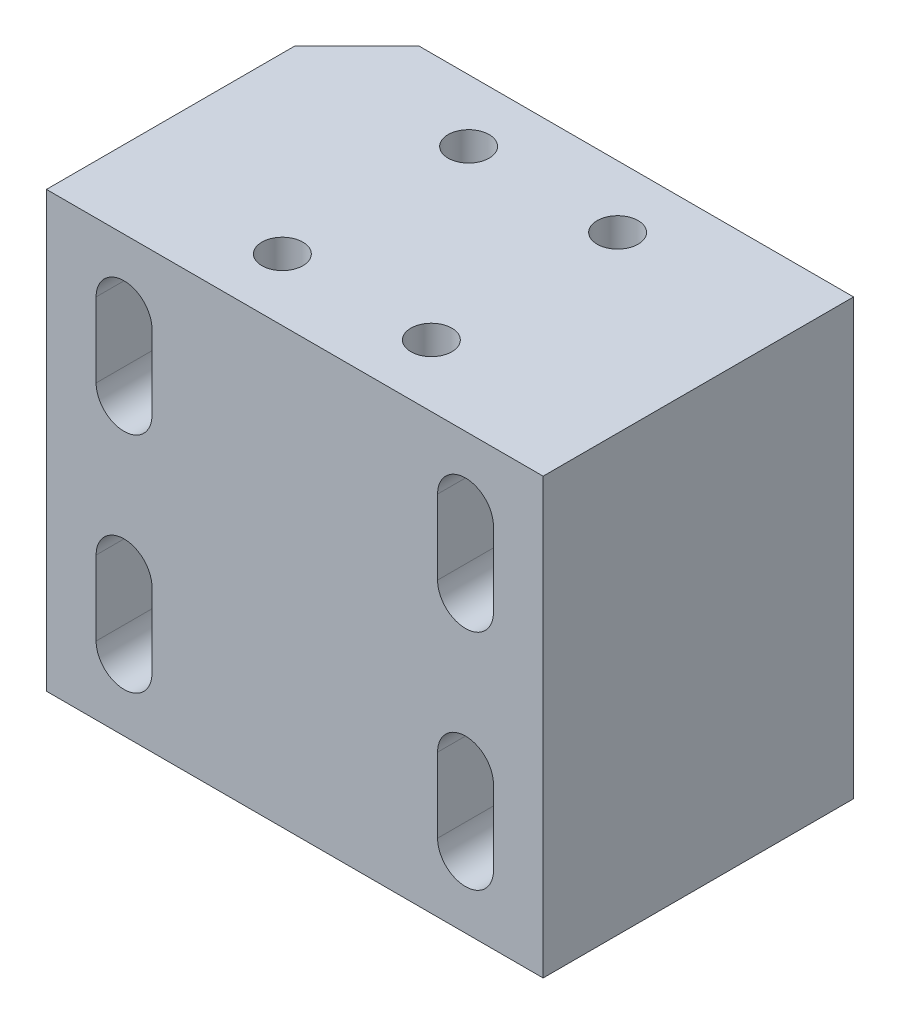
SolidWorks part; units mm, degrees
material "6061 Alloy"
ref_plane "Front Plane" through (0, 0, 0) normal (0, 0, 1) x (1, 0, 0)
ref_plane "Top Plane" through (0, 0, 0) normal (0, 1, 0) x (1, 0, 0)
ref_plane "Right Plane" through (0, 0, 0) normal (1, 0, 0) x (0, 0, -1)
sketch "Sketch1" plane through (0, 0, 0) normal (0, 0, 1) x (1, 0, 0)
  line L5 (-20, -17.5) -> (20, -17.5)
  line L6 (-20, -17.5) -> (-20, 17.5)
  line L7 (-20, 17.5) -> (20, 17.5)
  line L8 (20, -17.5) -> (20, 17.5)
  line L9 (-20, -17.5) -> (20, 17.5) construction
  line L10 (-20, 17.5) -> (20, -17.5) construction
  point P0 (0, 0)
  dimension "D1" = 35
  dimension "D2" = 40
extrude "Boss-Extrude1" add sketch "Sketch1" along normal blind 25 contours L7 L8 L5 L6
chamfer "Chamfer1" distance 5 angle 45 1 edges at (-20, 0, 0)
hole_wizard "CBORE for M4 Hexagon socket head cap screws1" positions "Sketch3" profile "Sketch4" counterbore size "M4" standard "GB" end condition through all
sketch "Sketch3" plane through (0, 0, 0) normal (0, 0, -1) x (-1, 0, 0)
  line L0 (-20, -17.5) -> (-20, 17.5) construction
  line L1 (15, 17.5) -> (-20, 17.5) construction
  line L2 (55, 0) -> (-55, 0) construction
  line L3 (0, 55) -> (0, -55) construction
  point P0 (-13.75, 9)
  point P13 (-13.75, -9)
  point P17 (13.75, -9)
  point P18 (13.75, 9)
  dimension "D1" = 6.25
  dimension "D2" = 8.5
sketch "Sketch4" plane through (13.75, 9, 0) normal (1, 0, 0) x (0, 1, 0)
  line L0 (0, 0) -> (0, 25)
  line L1 (0, 25) -> (2.25, 25)
  line L3 (2.25, 25) -> (2.25, 18)
  line L4 (2.25, 18) -> (4, 18)
  line L5 (4, 18) -> (4, 0)
  line L7 (4, 0) -> (0, 0)
  line L11 (0, -6.35) -> (0, 107.95) construction
  dimension "Thru Hole Dia." = 4.5
  dimension "Thru Hole Depth" = 25
  dimension "C'Bore Dia." = 8
  dimension "C'Bore Depth" = 18
sketch "Sketch5" plane through (0, 0, 18) normal (0, 0, -1) x (-1, 0, 0)
  line L0 (-13.75, 12) -> (-13.75, 6) construction
  line L1 (-9.75, 12) -> (-9.75, 6)
  line L2 (-17.75, 12) -> (-17.75, 6)
  line L3 (55, 0) -> (-55, 0) construction
  line L4 (-13.75, -12) -> (-13.75, -6) construction
  line L5 (-9.75, -12) -> (-9.75, -6)
  line L6 (-17.75, -12) -> (-17.75, -6)
  line L7 (0, 55) -> (0, -55) construction
  line L8 (13.75, 12) -> (13.75, 6) construction
  line L9 (9.75, 12) -> (9.75, 6)
  line L10 (17.75, 12) -> (17.75, 6)
  line L11 (13.75, -12) -> (13.75, -6) construction
  line L12 (9.75, -12) -> (9.75, -6)
  line L13 (17.75, -12) -> (17.75, -6)
  arc A0 (-9.75, 12) -> (-17.75, 12) centre (-13.75, 12) ccw
  arc A1 (-17.75, 6) -> (-9.75, 6) centre (-13.75, 6) ccw
  circle A2 centre (-13.75, 9) radius 4 construction
  arc A3 (-9.75, -12) -> (-17.75, -12) centre (-13.75, -12) cw
  arc A4 (-17.75, -6) -> (-9.75, -6) centre (-13.75, -6) cw
  arc A5 (9.75, 12) -> (17.75, 12) centre (13.75, 12) cw
  arc A6 (17.75, 6) -> (9.75, 6) centre (13.75, 6) cw
  arc A7 (9.75, -12) -> (17.75, -12) centre (13.75, -12) ccw
  arc A8 (17.75, -6) -> (9.75, -6) centre (13.75, -6) ccw
  point P2 (-13.75, 9)
  point P14 (-13.75, -9)
  point P23 (13.75, 9)
  point P30 (13.75, -9)
  dimension "D1" = 6
extrude "Cut-Extrude1" cut sketch "Sketch5" along normal through all
sketch "Sketch6" plane through (0, 0, 18) normal (0, 0, -1) x (-1, 0, 0)
  line L0 (-13.75, 12) -> (-13.75, 6) construction
  line L1 (-11.5, 12) -> (-11.5, 6)
  line L2 (-16, 12) -> (-16, 6)
  line L3 (0, 55) -> (0, -55) construction
  line L4 (13.75, 12) -> (13.75, 6) construction
  line L5 (11.5, 12) -> (11.5, 6)
  line L6 (16, 12) -> (16, 6)
  line L7 (55, 0) -> (-55, 0) construction
  line L8 (-13.75, -12) -> (-13.75, -6) construction
  line L9 (-11.5, -12) -> (-11.5, -6)
  line L10 (-16, -12) -> (-16, -6)
  line L11 (13.75, -12) -> (13.75, -6) construction
  line L12 (11.5, -12) -> (11.5, -6)
  line L13 (16, -12) -> (16, -6)
  arc A0 (-11.5, 12) -> (-16, 12) centre (-13.75, 12) ccw
  arc A1 (-16, 6) -> (-11.5, 6) centre (-13.75, 6) ccw
  circle A2 centre (-13.75, 9) radius 2.25 construction
  arc A3 (-9.75, 12) -> (-17.75, 12) centre (-13.75, 12) ccw construction
  arc A4 (11.5, 12) -> (16, 12) centre (13.75, 12) cw
  arc A5 (16, 6) -> (11.5, 6) centre (13.75, 6) cw
  arc A6 (-11.5, -12) -> (-16, -12) centre (-13.75, -12) cw
  arc A7 (-16, -6) -> (-11.5, -6) centre (-13.75, -6) cw
  arc A8 (11.5, -12) -> (16, -12) centre (13.75, -12) ccw
  arc A9 (16, -6) -> (11.5, -6) centre (13.75, -6) ccw
  point P2 (-13.75, 9)
  point P18 (13.75, 9)
  point P27 (-13.75, -9)
  point P34 (13.75, -9)
extrude "Cut-Extrude2" cut sketch "Sketch6" against normal through all
hole_wizard "M4 Tapped Hole1" positions "Sketch7" profile "Sketch8" tap size "M4" standard "GB" end condition through all
sketch "Sketch7" plane through (0, 17.5, 0) normal (0, 1, 0) x (1, 0, 0)
  line L0 (0, -13.75) -> (0, 13.75) construction
  line L1 (-20, -25) -> (20, -25) construction
  point P0 (-6, -5)
  point P4 (-6, -20)
  point P9 (6, -20)
  point P10 (6, -5)
  dimension "D1" = 15
  dimension "D2" = 12
  dimension "D3" = 5
sketch "Sketch8" plane through (-6, 17.5, 5) normal (1, 0, 0) x (0, 0, 1)
  line L0 (0, 0) -> (0, 35)
  line L1 (0, 35) -> (1.65, 35)
  line L2 (1.65, 35) -> (1.65, 0)
  line L5 (1.65, 0) -> (0, 0)
  line L11 (0, -6.35) -> (0, 107.95) construction
  dimension "Thru Tap Drill Dia." = 3.3
  dimension "Thru Tap Drill Depth" = 35
cosmetic thread "Hole Thread1" parameters "D2"=4
cosmetic thread "Hole Thread2" parameters "D2"=4
cosmetic thread "Hole Thread3" parameters "D2"=4
cosmetic thread "Hole Thread4" parameters "D2"=4
